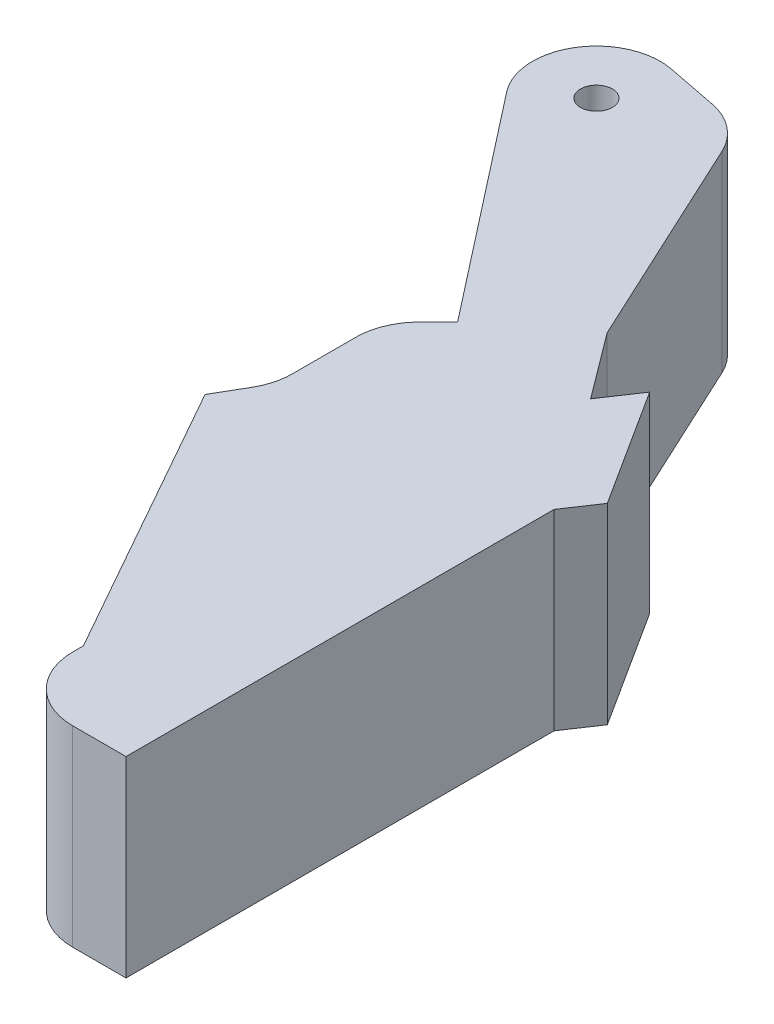
SolidWorks part; units mm, degrees
material "Gray Cast Iron (SN)"
ref_plane "Front" through (0, 0, 0) normal (0, 0, 1) x (1, 0, 0)
ref_plane "Top" through (0, 0, 0) normal (0, 1, 0) x (1, 0, 0)
ref_plane "Right" through (0, 0, 0) normal (1, 0, 0) x (0, 0, -1)
sketch "Sketch1" plane through (0, 0, 0) normal (0, 1, 0) x (1, 0, 0)
  line L0 (26.2981, -33.6826) -> (0, 0)
  line L1 (0, 0) -> (23.5491, -4.6305)
  line L2 (23.5491, -4.6305) -> (34.2089, -27.5654)
  line L3 (48.0785, -41.4146) -> (41.023, -30.384)
  line L5 (22.772, -37.2709) -> (22.772, -47.2709)
  line L6 (22.772, -47.2709) -> (20.3513, -51.4494)
  line L7 (20.3513, -51.4494) -> (35.0737, -77.5885)
  line L8 (35.0737, -77.5885) -> (35.0737, -84.5885)
  line L9 (35.0737, -84.5885) -> (46.0737, -84.5885)
  line L10 (46.0737, -84.5885) -> (46.0737, -44.4086)
  line L11 (46.0737, -44.4086) -> (48.0785, -41.4146)
  line L12 (34.2089, -27.5654) -> (38.8009, -33.7025)
  line L13 (38.8009, -33.7025) -> (41.023, -30.384)
  line L14 (26.2981, -33.6826) -> (22.772, -37.2709)
  dimension "D2" = 24
  dimension "D4" = 15
  dimension "D5" = 10
  dimension "D6" = 10
  dimension "D8" = 30
  dimension "D9" = 7
  dimension "D10" = 11
  dimension "D13" = 12
extrude "Boss-Extrude1" add sketch "Sketch1" along normal mid plane 18 contours L0 L1 L2 L12 L13 L3 L11 L10 L9 L8 L7 L6 L5 L14
fillet "Fillet1" radius 6 2 edges at (23.5491, 0, 4.6305) (0, 0, 0)
fillet "Fillet2" radius 6 2 edges at (22.772, 0, 37.2709) (22.772, 0, 47.2709)
fillet "Fillet3" radius 6 1 edges at (35.0737, 0, 84.5885)
sketch "Sketch4" plane through (0, 9, 0) normal (0, 1, 0) x (1, 0, 0)
  circle A0 centre (14.633, -8.9922) radius 1.5
  dimension "D1" = 3
extrude "Cut-Extrude2" cut sketch "Sketch4" against normal through all
